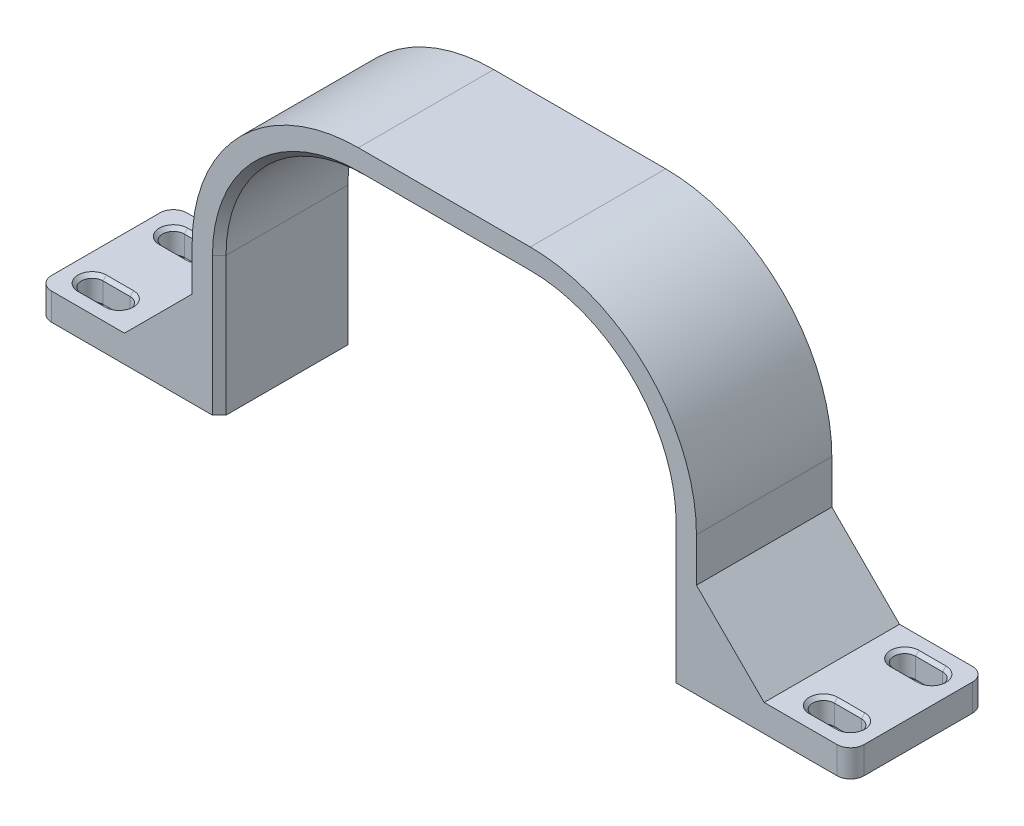
SolidWorks part; units mm, degrees
ref_plane "Front Plane" through (0, 0, 0) normal (0, 0, 1) x (1, 0, 0)
ref_plane "Top Plane" through (0, 0, 0) normal (0, 1, 0) x (1, 0, 0)
ref_plane "Right Plane" through (0, 0, 0) normal (1, 0, 0) x (0, 0, -1)
sketch "Sketch1" plane through (0, 0, 0) normal (0, 0, 1) x (1, 0, 0)
  line L0 (12.7, 20.447) -> (-12.7, 20.447) construction
  line L1 (12.7, 20.447) -> (-12.7, 20.447) construction
  line L2 (33.147, 0) -> (-33.147, 0) construction
  line L3 (12.7, 20.547) -> (-12.7, 20.547)
  line L4 (-33.247, 0) -> (-33.247, -20.447)
  line L5 (58.015, -20.447) -> (-58.015, -20.447) construction
  line L6 (-33.247, -20.447) -> (-60.015, -20.447)
  line L7 (33.247, 0) -> (33.247, -20.447)
  line L8 (33.247, -20.447) -> (60.015, -20.447)
  line L9 (37.247, -16.447) -> (60.015, -16.447)
  line L10 (37.247, 0) -> (37.247, -16.447)
  line L11 (12.7, 24.547) -> (-12.7, 24.547)
  line L12 (-37.247, 0) -> (-37.247, -16.447)
  line L13 (-37.247, -16.447) -> (-60.015, -16.447)
  line L14 (-60.015, -20.447) -> (-60.015, -16.447)
  line L15 (60.015, -20.447) -> (60.015, -16.447)
  arc A0 (12.7, -20.447) -> (12.7, 20.447) centre (12.7, 0) ccw construction
  arc A1 (-12.7, 20.447) -> (-12.7, -20.447) centre (-12.7, 0) ccw construction
  arc A2 (33.147, 0) -> (12.7, 20.447) centre (12.7, 0) ccw construction
  arc A3 (-12.7, 20.447) -> (-33.147, 0) centre (-12.7, 0) ccw construction
  arc A4 (33.247, 0) -> (12.7, 20.547) centre (12.7, 0) ccw
  arc A5 (-12.7, 20.547) -> (-33.247, 0) centre (-12.7, 0) ccw
  arc A6 (37.247, 0) -> (12.7, 24.547) centre (12.7, 0) ccw
  arc A7 (-12.7, 24.547) -> (-37.247, 0) centre (-12.7, 0) ccw
  dimension "D1" = 0.1
  dimension "D2" = 4
extrude "Boss-Extrude1" add sketch "Sketch1" along normal blind 20
fillet "Fillet1" radius 2 4 edges at (60.015, -18.447, 0) (60.015, -18.447, 20) (-60.015, -18.447, 20) (-60.015, -18.447, 0)
sketch "Sketch3" plane through (0, -16.447, 0) normal (0, 1, 0) x (1, 0, 0)
  line L0 (52.015, -2.4) -> (56.015, -2.4) construction
  line L1 (56.015, -5.6) -> (52.015, -5.6) construction
  line L2 (56.015, -17.6) -> (52.015, -17.6) construction
  line L3 (52.015, -14.4) -> (56.015, -14.4) construction
  line L4 (-52.015, -5.6) -> (-56.015, -5.6) construction
  line L5 (-56.015, -2.4) -> (-52.015, -2.4) construction
  line L6 (-56.015, -14.4) -> (-52.015, -14.4) construction
  line L7 (-52.015, -17.6) -> (-56.015, -17.6) construction
  line L8 (52.015, -2.4) -> (56.015, -2.4)
  line L9 (56.015, -5.6) -> (52.015, -5.6)
  line L10 (56.015, -17.6) -> (52.015, -17.6)
  line L11 (52.015, -14.4) -> (56.015, -14.4)
  line L12 (-52.015, -5.6) -> (-56.015, -5.6)
  line L13 (-56.015, -2.4) -> (-52.015, -2.4)
  line L14 (-56.015, -14.4) -> (-52.015, -14.4)
  line L15 (-52.015, -17.6) -> (-56.015, -17.6)
  arc A0 (52.015, -2.4) -> (52.015, -5.6) centre (52.015, -4) ccw construction
  arc A1 (56.015, -5.6) -> (56.015, -2.4) centre (56.015, -4) ccw construction
  arc A2 (56.015, -17.6) -> (56.015, -14.4) centre (56.015, -16) ccw construction
  arc A3 (52.015, -14.4) -> (52.015, -17.6) centre (52.015, -16) ccw construction
  arc A4 (-52.015, -5.6) -> (-52.015, -2.4) centre (-52.015, -4) ccw construction
  arc A5 (-56.015, -2.4) -> (-56.015, -5.6) centre (-56.015, -4) ccw construction
  arc A6 (-52.015, -17.6) -> (-52.015, -14.4) centre (-52.015, -16) ccw construction
  arc A7 (-56.015, -14.4) -> (-56.015, -17.6) centre (-56.015, -16) ccw construction
  arc A8 (52.015, -2.4) -> (52.015, -5.6) centre (52.015, -4) ccw
  arc A9 (56.015, -5.6) -> (56.015, -2.4) centre (56.015, -4) ccw
  arc A10 (56.015, -17.6) -> (56.015, -14.4) centre (56.015, -16) ccw
  arc A11 (52.015, -14.4) -> (52.015, -17.6) centre (52.015, -16) ccw
  arc A12 (-52.015, -5.6) -> (-52.015, -2.4) centre (-52.015, -4) ccw
  arc A13 (-56.015, -2.4) -> (-56.015, -5.6) centre (-56.015, -4) ccw
  arc A14 (-52.015, -17.6) -> (-52.015, -14.4) centre (-52.015, -16) ccw
  arc A15 (-56.015, -14.4) -> (-56.015, -17.6) centre (-56.015, -16) ccw
extrude "Cut-Extrude1" cut sketch "Sketch3" against normal through all
chamfer "Chamfer1" distance 0.5 angle 45 32 edges at (-54.015, -16.447, 2.4) (-57.615, -16.447, 4) (-50.415, -16.447, 4) (-54.015, -16.447, 5.6) (-54.015, -16.447, 14.4) (-57.615, -16.447, 16) (-50.415, -16.447, 16) (-54.015, -16.447, 17.6) (-50.415, -20.447, 16) (-54.015, -20.447, 14.4) (-54.015, -20.447, 17.6) (-57.615, -20.447, 16) (-54.015, -20.447, 2.4) (-57.615, -20.447, 4) (-50.415, -20.447, 4) (-54.015, -20.447, 5.6) (54.015, -20.447, 2.4) (50.415, -20.447, 4) (57.615, -20.447, 4) (54.015, -20.447, 5.6) (54.015, -20.447, 14.4) (50.415, -20.447, 16) (57.615, -20.447, 16) (54.015, -20.447, 17.6) (54.015, -16.447, 2.4) (50.415, -16.447, 4) (57.615, -16.447, 4) (54.015, -16.447, 5.6) (54.015, -16.447, 14.4) (50.415, -16.447, 16) (57.615, -16.447, 16) (54.015, -16.447, 17.6)
chamfer "Chamfer2" distance 10 angle 45 2 edges at (37.247, -16.447, 10) (-37.247, -16.447, 10)
chamfer "Chamfer3" distance 1 angle 45 10 edges at (33.247, -10.2235, 20) (27.2289, 14.5289, 20) (0, 20.547, 20) (-27.2289, 14.5289, 20) (-33.247, -10.2235, 20) (33.247, -10.2235, 0) (27.2289, 14.5289, 0) (-33.247, -10.2235, 0) (0, 20.547, 0) (-27.2289, 14.5289, 0)
